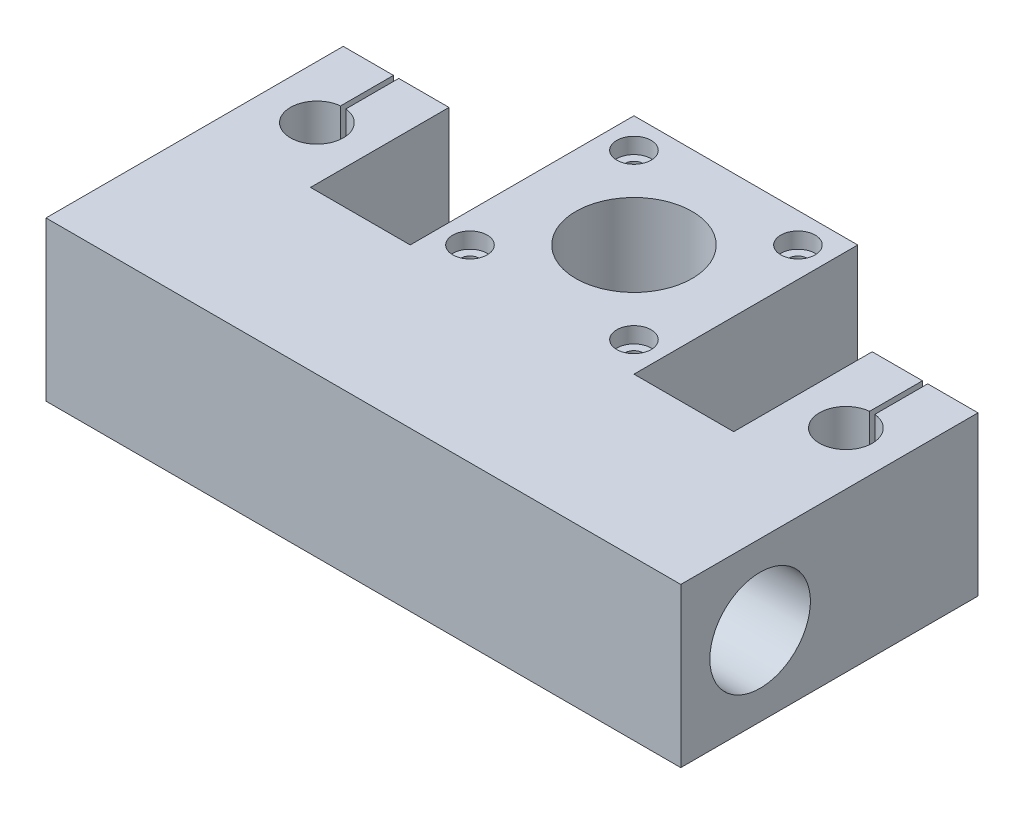
SolidWorks part; units mm, degrees
ref_plane "Спереди" through (0, 0, 0) normal (0, 0, 1) x (1, 0, 0)
ref_plane "Сверху" through (0, 0, 0) normal (0, 1, 0) x (1, 0, 0)
ref_plane "Справа" through (0, 0, 0) normal (1, 0, 0) x (0, 0, -1)
sketch "Эскиз3" plane through (0, 0, 0) normal (0, 1, 0) x (1, 0, 0)
  line L0 (0, 72.3) -> (0, 0) construction
  line L1 (0, 0) -> (-60, 0)
  line L4 (-60, 0) -> (-60, 56.1881)
  line L5 (-60, 56.1881) -> (-50.5, 56.1881)
  line L6 (-40, 56.1881) -> (-40, 30)
  line L7 (-40, 30) -> (-21.15, 30)
  line L8 (-21.15, 30) -> (-21.15, 72.3)
  line L9 (-21.15, 72.3) -> (21.15, 72.3)
  line L10 (21.15, 72.3) -> (21.15, 30)
  line L11 (21.15, 30) -> (40, 30)
  line L12 (40, 30) -> (40, 56.1881)
  line L13 (-40, 56.1881) -> (-49.5, 56.1881)
  line L14 (60, 56.1881) -> (60, 0)
  line L17 (60, 0) -> (0, 0)
  line L18 (-49.5, 56.1881) -> (-49.5, 46.1881)
  line L19 (-50.5, 56.1881) -> (-50.5, 46.1881)
  line L20 (40, 56.1881) -> (49.5, 56.1881)
  line L21 (60, 56.1881) -> (50.5, 56.1881)
  line L22 (50.5, 56.1881) -> (50.5, 46.1881)
  line L23 (49.5, 56.1881) -> (49.5, 46.1881)
  arc A0 (-50.5, 46.1881) -> (-49.5, 46.1881) centre (-50, 41.2131) ccw
  arc A1 (49.5, 46.1881) -> (50.5, 46.1881) centre (50, 41.2131) ccw
  circle A2 centre (0, 51.15) radius 11
  point P1 (-48.1652, 19.4028)
  point P6 (0, 0)
  point P7 (0, 0)
  point P16 (0, 0)
  point P18 (0, 0)
  point P19 (60, 0)
  point P28 (-47.7885, 20.5465)
  point P33 (-46.9825, 21.8024)
  point P35 (0, 42.3)
  point P36 (-47.7417, 21.15)
  point P37 (0, 0)
  point P38 (0, 25.0251)
  point P39 (0, 0)
  point P40 (0, 0)
  point P43 (0, 0)
  point P44 (0, 0)
  point P45 (-5.3465, 25.0251)
  point P46 (0, 0)
  point P47 (0, 0)
  point P48 (0, 0)
  point P49 (0, 0)
  point P50 (0, 0)
  point P51 (0, 0)
  point P52 (0, 42.3)
  point P53 (0, 0)
  point P54 (0, 0)
  point P55 (0, 0)
  point P56 (0, 0)
  point P57 (0, 0)
  point P58 (0, 0)
  point P60 (0, 0)
  point P61 (0, 0)
  point P62 (0, 25.0251)
  point P63 (0, 0)
  point P64 (0, 21.15)
  point P65 (-47.2027, 25.0251)
  point P66 (-47.8327, 21.15)
  point P67 (60, 11.2359)
  point P68 (60, 12.2057)
  point P69 (-60, 10.8515)
  point P70 (0, 0)
  point P71 (-60, 10.9869)
  point P72 (-57.5241, 11.3931)
  point P73 (62.948, 12.1109)
  point P74 (-57.6325, 13.2484)
  point P75 (0, 0)
  point P76 (0, 0)
  point P77 (0, 0)
  point P78 (-57.6325, 12.2734)
  point P79 (-57.795, 8.8607)
  point P80 (-57.795, -1.1393)
  point P81 (-57.795, -1.1393)
  point P82 (0, 0)
  dimension "D7" = 5
  dimension "D10" = 10
  dimension "D11" = 100
  dimension "D13" = 22
  dimension "D2" = 21.15
  dimension "D3" = 42.3
  dimension "D4" = 42.3
  dimension "D5" = 30
  dimension "D6" = 1
extrude "Бобышка-Вытянуть1" add sketch "Эскиз3" along normal blind 30
hole_wizard "Цековка для винта с внутренним шестигранником M32" positions "Эскиз6" profile "Эскиз7" counterbore size "M3" standard "Ansi Metric" end condition through all
sketch "Эскиз6" plane through (0, 30, 0) normal (0, 1, 0) x (1, 0, 0)
  line L0 (0, 72.3) -> (0, 0) construction
  line L1 (21.15, 72.3) -> (-21.15, 72.3) construction
  line L3 (-21.15, 51.15) -> (21.15, 51.15) construction
  line L4 (-21.15, 72.3) -> (-21.15, 30) construction
  line L5 (21.15, 30) -> (21.15, 72.3) construction
  point P0 (-15.5, 66.65)
  point P2 (15.5, 66.65)
  point P4 (15.5, 35.65)
  point P6 (-15.5, 35.65)
  dimension "D1" = 31
  dimension "D2" = 31
  dimension "D3" = 21.15
sketch "Эскиз7" plane through (-15.5, 30, -66.65) normal (1, 0, 0) x (0, 0, 1)
  line L0 (0, 0) -> (0, 30)
  line L1 (0, 30) -> (1.7, 30)
  line L3 (1.7, 30) -> (1.7, 3)
  line L4 (1.7, 3) -> (3.25, 3)
  line L5 (3.25, 3) -> (3.25, 0)
  line L7 (3.25, 0) -> (0, 0)
  line L11 (0, -6.35) -> (0, 107.95) construction
  dimension "Диаметр сквозного отверстия" = 3.4
  dimension "Глубина сквозного отверстия" = 30
  dimension "Диаметр цековки" = 6.5
  dimension "Глубина цековки" = 3
sketch "Эскиз15" plane through (-60, 0, 0) normal (-1, 0, 0) x (0, 0, 1)
  line L1 (-56.1881, 30) -> (0, 30) construction
  line L2 (0, 30) -> (0, 0) construction
  circle A0 centre (-15, 15) radius 9.5
  point P2 (-10.0792, 10.0593)
  point P3 (-12.4083, 14.9718)
  point P4 (0, 0)
  dimension "D1" = 19
  dimension "D2" = 15
  dimension "D3" = 15
extrude "Вырез-Вытянуть1" cut sketch "Эскиз15" against normal through all contours A0
